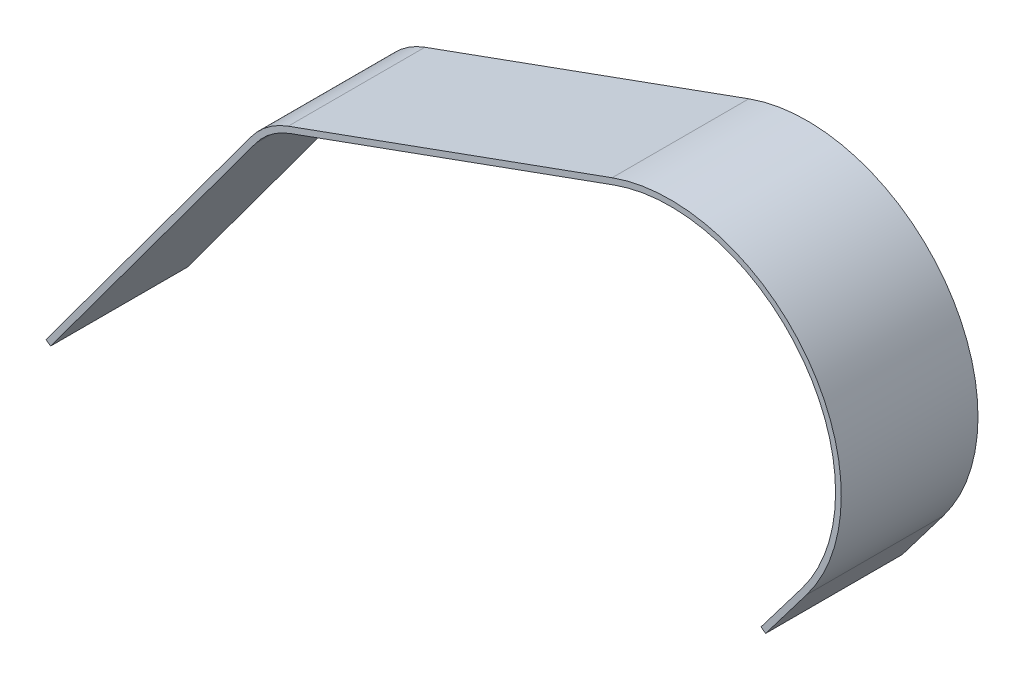
SolidWorks part; units mm, degrees
material "AISI 1020"
ref_plane "Front Plane" through (0, 0, 0) normal (0, 0, 1) x (1, 0, 0)
ref_plane "Top Plane" through (0, 0, 0) normal (0, 1, 0) x (1, 0, 0)
ref_plane "Right Plane" through (0, 0, 0) normal (1, 0, 0) x (0, 0, -1)
sketch "Sketch1" plane through (0, 0, 0) normal (0, 0, 1) x (1, 0, 0)
  line L0 (-36.5682, 0.9207) -> (143.9526, 66.3011)
  line L1 (-21.4316, -40.8727) -> (13.1807, -28.3369) construction
  line L6 (-36.5682, 0.9207) -> (-21.4316, -40.8727) construction
  line L14 (229.4691, -110.8747) -> (252.2647, -80.8348)
  line L15 (239.0655, -98.2286) -> (240.3301, -99.1882) construction
  line L19 (-57.2078, -14.4934) -> (-171.5307, -169.5402)
  line L23 (-163.3872, -155.8209) -> (-162.1095, -156.763) construction
  line L28 (143.9526, 66.3011) -> (194.1881, -72.4034) construction
  arc A0 (-57.2078, -14.4934) -> (-36.5682, 0.9207) centre (-21.4316, -40.8727) cw
  arc A10 (-190.1171, -186.0404) -> (-190.1067, -160.6404) centre (-190.1119, -173.3404) ccw construction
  arc A11 (143.9526, 66.3011) -> (252.2647, -80.8348) centre (176.3881, -23.2561) cw
  circle A12 centre (-21.4316, -40.8727) radius 6 construction
  circle A13 centre (231.071, -129.7727) radius 12.7 construction
  dimension "D5" = 44.45
  dimension "D3" = 15.875
  dimension "D2" = 95.25
  dimension "D1" = 15.875
extrude "Extrude-Thin1" add sketch "Sketch1" along normal blind 76.2 thin
